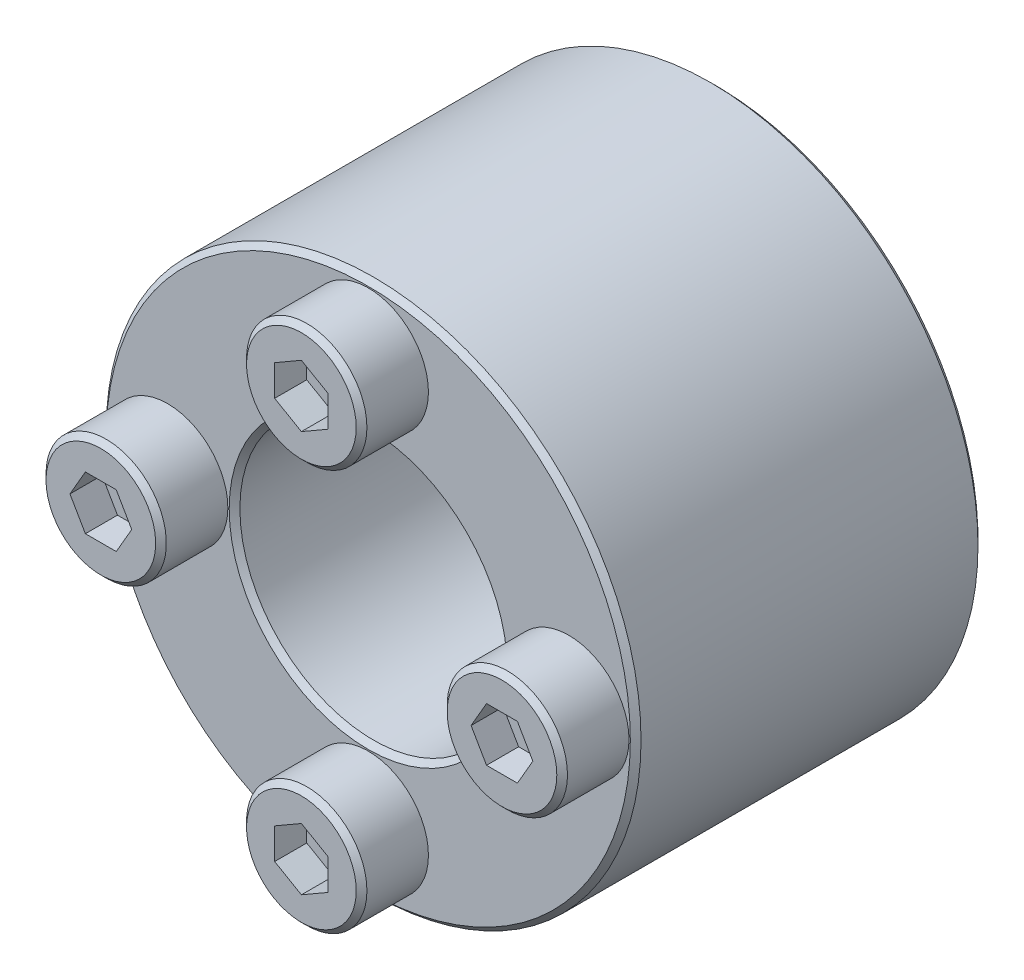
SolidWorks part; units mm, degrees
material "6061 合金"
ref_plane "前视基准面" through (0, 0, 0) normal (0, 0, 1) x (1, 0, 0)
ref_plane "上视基准面" through (0, 0, 0) normal (0, 1, 0) x (1, 0, 0)
ref_plane "右视基准面" through (0, 0, 0) normal (1, 0, 0) x (0, 0, -1)
other "Configuration Table"
ref_plane "基准面1" through (0, 0, 0) normal (0, -1, 0) x (1, 0, 0)
sketch "草图1" plane through (0, 0, 0) normal (0, -1, 0) x (1, 0, 0)
  line L0 (10, 13) -> (0, 13)
  line L1 (0, 13) -> (0, 0)
  line L2 (0, 0) -> (10, 0)
  line L3 (10, 0) -> (10, 13)
  line L4 (0, 13) -> (0, 0) construction
revolve "旋转1" add sketch "草图1" angle 360 about L4
sketch "草图2" plane through (0, 0, 13) normal (0, 0, 1) x (1, 0, 0)
  circle A0 centre (-7.5, 0) radius 2.25
extrude "凸台-拉伸1" add sketch "草图2" along normal blind 2.5
sketch "草图3" plane through (0, 0, 15.5) normal (0, 0, 1) x (1, 0, 0)
  line L0 (-6.9226, 1) -> (-8.0774, 1)
  line L1 (-8.0774, 1) -> (-8.6547, 0)
  line L2 (-8.6547, 0) -> (-8.0774, -1)
  line L3 (-8.0774, -1) -> (-6.9226, -1)
  line L4 (-6.9226, -1) -> (-6.3453, 0)
  line L5 (-6.3453, 0) -> (-6.9226, 1)
extrude "切除-拉伸1" cut sketch "草图3" against normal blind 1.2
sketch "草图4" plane through (0, 0, 13) normal (0, 0, 1) x (1, 0, 0)
  circle A0 centre (0, -7.5) radius 2.25
extrude "凸台-拉伸2" add sketch "草图4" along normal blind 2.5
sketch "草图5" plane through (0, 0, 15.5) normal (0, 0, 1) x (1, 0, 0)
  line L0 (-1, -6.9226) -> (-1, -8.0774)
  line L1 (-1, -8.0774) -> (0, -8.6547)
  line L2 (0, -8.6547) -> (1, -8.0774)
  line L3 (1, -8.0774) -> (1, -6.9226)
  line L4 (1, -6.9226) -> (0, -6.3453)
  line L5 (0, -6.3453) -> (-1, -6.9226)
extrude "切除-拉伸2" cut sketch "草图5" against normal blind 1.2
sketch "草图6" plane through (0, 0, 13) normal (0, 0, 1) x (1, 0, 0)
  circle A0 centre (7.5, 0) radius 2.25
extrude "凸台-拉伸3" add sketch "草图6" along normal blind 2.5
sketch "草图7" plane through (0, 0, 15.5) normal (0, 0, 1) x (1, 0, 0)
  line L0 (6.9226, -1) -> (8.0774, -1)
  line L1 (8.0774, -1) -> (8.6547, 0)
  line L2 (8.6547, 0) -> (8.0774, 1)
  line L3 (8.0774, 1) -> (6.9226, 1)
  line L4 (6.9226, 1) -> (6.3453, 0)
  line L5 (6.3453, 0) -> (6.9226, -1)
extrude "切除-拉伸3" cut sketch "草图7" against normal blind 1.2
sketch "草图8" plane through (0, 0, 13) normal (0, 0, 1) x (1, 0, 0)
  circle A0 centre (0, 7.5) radius 2.25
extrude "凸台-拉伸4" add sketch "草图8" along normal blind 2.5
sketch "草图9" plane through (0, 0, 15.5) normal (0, 0, 1) x (1, 0, 0)
  line L0 (1, 6.9226) -> (1, 8.0774)
  line L1 (1, 8.0774) -> (0, 8.6547)
  line L2 (0, 8.6547) -> (-1, 8.0774)
  line L3 (-1, 8.0774) -> (-1, 6.9226)
  line L4 (-1, 6.9226) -> (0, 6.3453)
  line L5 (0, 6.3453) -> (1, 6.9226)
extrude "切除-拉伸4" cut sketch "草图9" against normal blind 1.2
ref_plane "基准面2" through (0, 7.5, 0) normal (0, 1, 0) x (1, 0, 0)
sketch "草图10" plane through (0, 7.5, 0) normal (0, 1, 0) x (1, 0, 0)
  line L0 (1.1, -2) -> (0, -2)
  line L1 (0, -2) -> (0, -13)
  line L2 (0, -13) -> (1.1, -13)
  line L3 (1.1, -13) -> (1.1, -2)
  line L4 (0, -2) -> (0, -13) construction
revolve "切除-旋转1" cut sketch "草图10" angle 360 about L4
sketch "草图11" plane through (0, 0, 0) normal (0, 1, 0) x (1, 0, 0)
  line L0 (8.6, -2) -> (7.5, -2)
  line L1 (7.5, -2) -> (7.5, -13)
  line L2 (7.5, -13) -> (8.6, -13)
  line L3 (8.6, -13) -> (8.6, -2)
  line L4 (7.5, -2) -> (7.5, -13) construction
revolve "切除-旋转2" cut sketch "草图11" angle 360 about L4
ref_plane "基准面3" through (0, -7.5, 0) normal (0, 1, 0) x (1, 0, 0)
sketch "草图12" plane through (0, -7.5, 0) normal (0, 1, 0) x (1, 0, 0)
  line L0 (1.1, -2) -> (0, -2)
  line L1 (0, -2) -> (0, -13)
  line L2 (0, -13) -> (1.1, -13)
  line L3 (1.1, -13) -> (1.1, -2)
  line L4 (0, -2) -> (0, -13) construction
revolve "切除-旋转3" cut sketch "草图12" angle 360 about L4
sketch "草图13" plane through (0, 0, 0) normal (0, 1, 0) x (1, 0, 0)
  line L0 (-6.4, -2) -> (-7.5, -2)
  line L1 (-7.5, -2) -> (-7.5, -13)
  line L2 (-7.5, -13) -> (-6.4, -13)
  line L3 (-6.4, -13) -> (-6.4, -2)
  line L4 (-7.5, -2) -> (-7.5, -13) construction
revolve "切除-旋转4" cut sketch "草图13" angle 360 about L4
hole_wizard "Ø10.0 (10) 直径孔1" positions "草图15" profile "草图14" hole size "Ø10.0" standard "ANSI Metric"
sketch "草图15" plane through (0, 0, 0) normal (0, 0, -1) x (-1, 0, 0)
  point P0 (0, 0)
sketch "草图14" plane through (0, 0, 0) normal (1, 0, 0) x (0, 1, 0)
  line L0 (0, 0) -> (0, 15.5)
  line L1 (0, 15.5) -> (5, 15.5)
  line L2 (5, 15.5) -> (5, 0)
  line L5 (5, 0) -> (0, 0)
  line L11 (0, -6.35) -> (0, 107.95) construction
  dimension "通孔孔直径" = 10
  dimension "通孔孔深度" = 15.5
chamfer "倒角1" distance 0.2 angle 45 8 edges at (-10, 0, 0) (5, 0, 13) (-10, 0, 13) (-5.25, 0, 15.5) (-5, 0, 0) (2.25, -7.5, 15.5) (2.25, 7.5, 15.5) (9.75, 0, 15.5)
